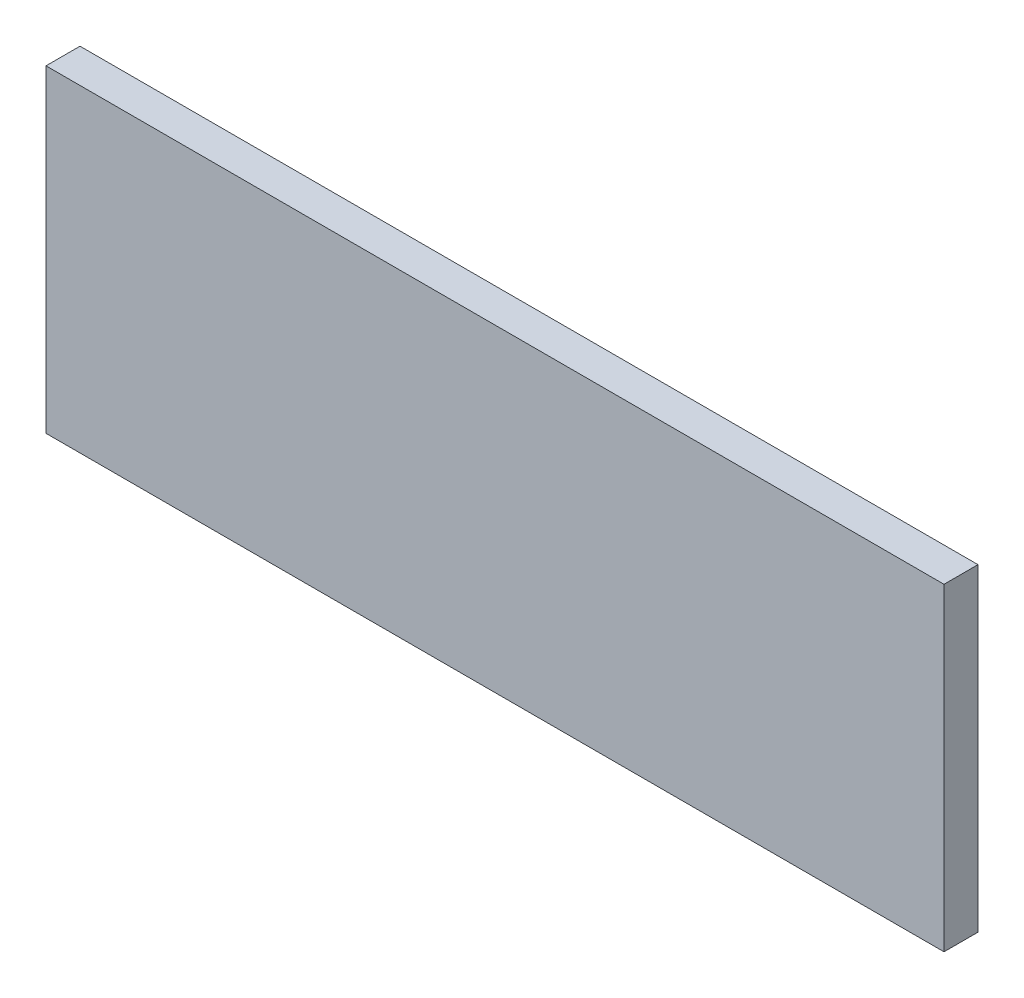
SolidWorks part; units mm, degrees
material "Copper"
ref_plane "Front Plane" through (0, 0, 0) normal (0, 0, 1) x (1, 0, 0)
ref_plane "Top Plane" through (0, 0, 0) normal (0, 1, 0) x (1, 0, 0)
ref_plane "Right Plane" through (0, 0, 0) normal (1, 0, 0) x (0, 0, -1)
sketch "Sketch1" plane through (0, 0, 0) normal (0, 0, 1) x (1, 0, 0)
  line L1 (-33.5437, 11.8902) -> (33.5437, 11.8902)
  line L2 (-33.5437, 11.8902) -> (-33.5437, -11.8902)
  line L3 (-33.5437, -11.8902) -> (33.5437, -11.8902)
  line L4 (33.5437, 11.8902) -> (33.5437, -11.8902)
  line L5 (-33.5437, 11.8902) -> (33.5437, -11.8902) construction
  line L6 (-33.5437, -11.8902) -> (33.5437, 11.8902) construction
  point P0 (0, 0)
extrude "Boss-Extrude1" add sketch "Sketch1" along normal blind 2.54
